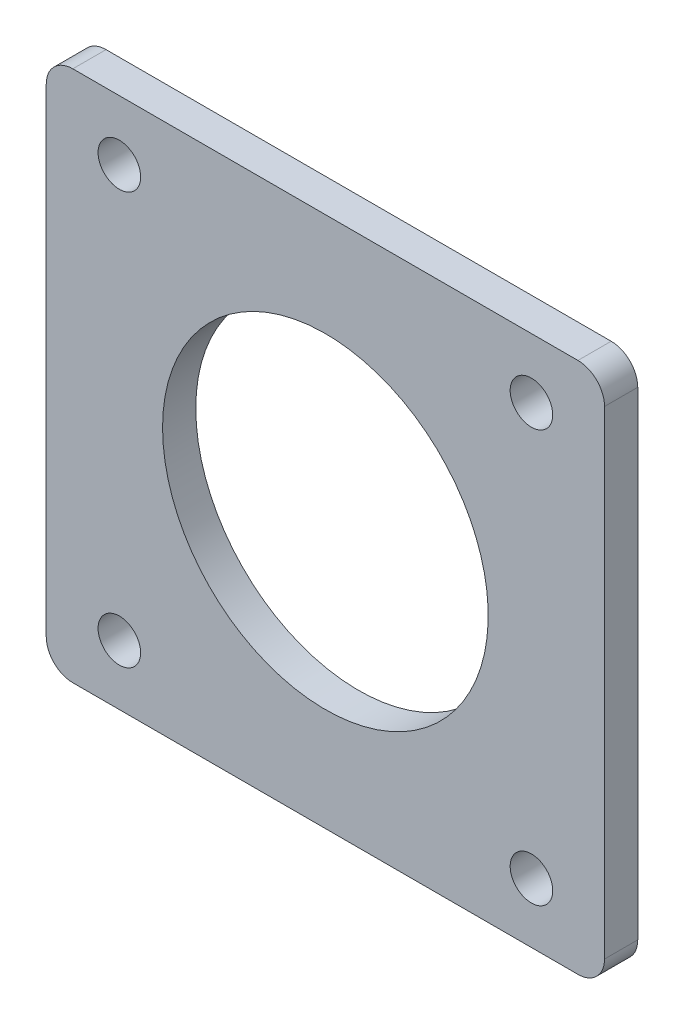
SolidWorks part; units mm, degrees
ref_plane "Front Plane" through (0, 0, 0) normal (0, 0, 1) x (1, 0, 0)
ref_plane "Top Plane" through (0, 0, 0) normal (0, 1, 0) x (1, 0, 0)
ref_plane "Right Plane" through (0, 0, 0) normal (1, 0, 0) x (0, 0, -1)
ref_plane "Plane1" through (0, 0, 1.25) normal (0, 0, 1) x (1, 0, 0)
sketch "Sketch1" plane through (0, 0, 1.25) normal (0, 0, 1) x (1, 0, 0)
  line L0 (-21, 18) -> (-21, -18)
  line L1 (-19, -20) -> (19, -20)
  line L2 (21, -18) -> (21, 18)
  line L3 (19, 20) -> (-19, 20)
  circle A1 centre (-15.5, 15.5) radius 1.6
  circle A2 centre (15.5, -15.5) radius 1.6
  arc A3 (-21, -18) -> (-19, -20) centre (-19, -18) ccw
  arc A4 (19, -20) -> (21, -18) centre (19, -18) ccw
  arc A5 (21, 18) -> (19, 20) centre (19, 18) ccw
  arc A6 (-19, 20) -> (-21, 18) centre (-19, 18) ccw
  circle A7 centre (0, 0) radius 12.25
  circle A8 centre (-15.5, -15.5) radius 1.6
  circle A9 centre (15.5, 15.5) radius 1.6
  point P0 (0, 0)
  dimension "D1" = 2
  dimension "D2" = 2
  dimension "D3" = 2
  dimension "D4" = 2
  dimension "D5" = 24.5
  dimension "D6" = 40
  dimension "D7" = 20
  dimension "D8" = 4.5
  dimension "D9" = 31
  dimension "D10" = 4.5
  dimension "D11" = 31
extrude "Boss-Extrude1" add sketch "Sketch1" against normal blind 2.5
